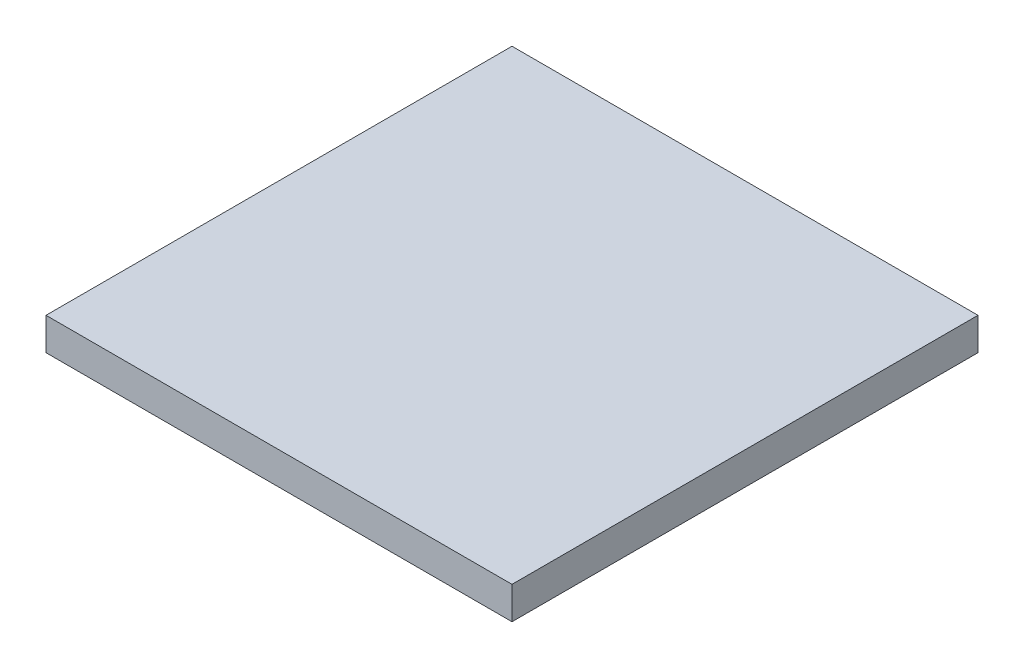
SolidWorks part; units mm, degrees
ref_plane "Front Plane" through (0, 0, 0) normal (0, 0, 1) x (1, 0, 0)
ref_plane "Top Plane" through (0, 0, 0) normal (0, 1, 0) x (1, 0, 0)
ref_plane "Right Plane" through (0, 0, 0) normal (1, 0, 0) x (0, 0, -1)
sketch "Sketch1" plane through (0, 0, 0) normal (0, 1, 0) x (1, 0, 0)
  line L1 (-11.5, -11.5) -> (11.5, -11.5)
  line L2 (-11.5, -11.5) -> (-11.5, 11.5)
  line L3 (-11.5, 11.5) -> (11.5, 11.5)
  line L4 (11.5, -11.5) -> (11.5, 11.5)
extrude "Plate_Extrude" add sketch "Sketch1" along normal blind 1.6
equation "\"ValveDiameter\" = 50mm"
equation "\"MotorGearTeeth\" = 40"
equation "\"OutputGearTeeth\" = 80"
equation "\"GearModule\" = 1.5mm"
equation "\"PressureAngle\" = 20deg"
equation "\"GearCenterDistance\" = 90mm"
equation "\"GearWidth\" = 18mm"
equation "\"OutputShaftDiameter\" = 20mm"
equation "\"BearingOD\" = 47mm"
equation "\"BearingWidth\" = 14mm"
equation "\"PlateThickness\" = 6mm"
equation "\"ValveRotation\" = 90deg"
